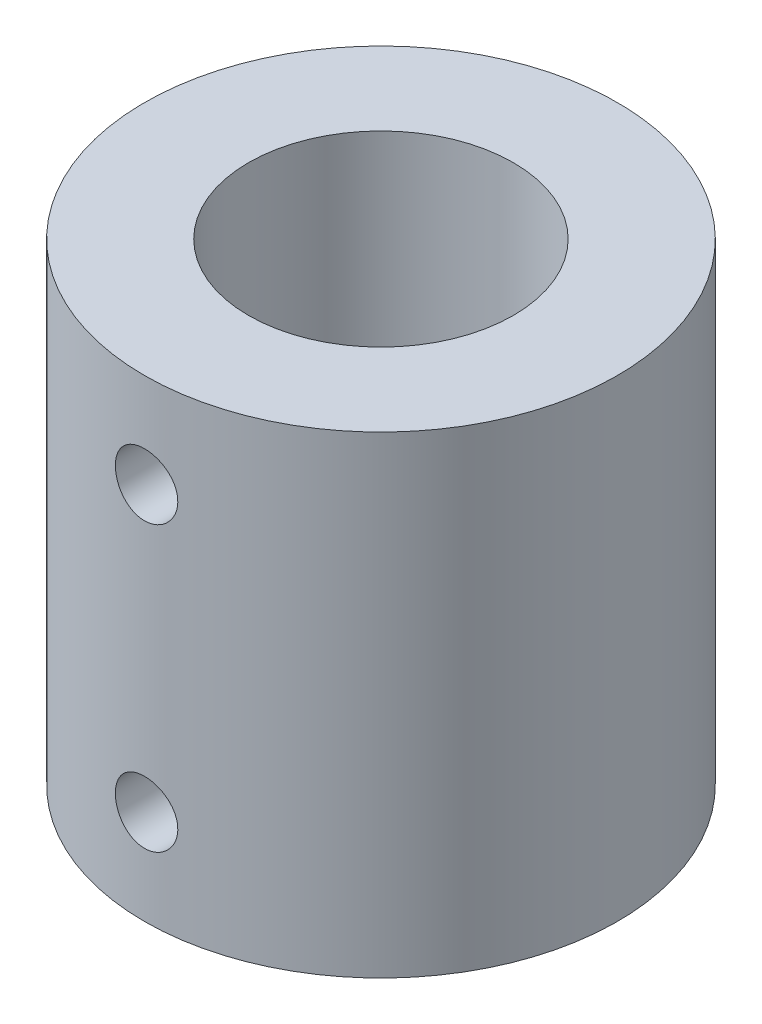
SolidWorks part; units mm, degrees
material "6061 Alloy"
ref_plane "Front Plane" through (0, 0, 0) normal (0, 0, 1) x (1, 0, 0)
ref_plane "Top Plane" through (0, 0, 0) normal (0, 1, 0) x (1, 0, 0)
ref_plane "Right Plane" through (0, 0, 0) normal (1, 0, 0) x (0, 0, -1)
sketch "Sketch1" plane through (0, 0, 0) normal (0, 1, 0) x (1, 0, 0)
  circle A0 centre (0, 0) radius 12.5
  circle A1 centre (0, 0) radius 3
  dimension "D1" = 25
  dimension "D2" = 6
extrude "Boss-Extrude1" add sketch "Sketch1" along normal blind 25
sketch "Sketch2" plane through (0, 25, 0) normal (0, 1, 0) x (1, 0, 0)
  circle A0 centre (0, 0) radius 7
  dimension "D1" = 14
extrude "Cut-Extrude1" cut sketch "Sketch2" against normal blind 12.5
sketch "Sketch3" plane through (0, 0, 0) normal (0, 0, 1) x (1, 0, 0)
  line L0 (0, 20) -> (0, 5) construction
  line L1 (-12.5, 25) -> (-12.5, 0) construction
  circle A0 centre (0, 5) radius 1.65
  circle A1 centre (0, 20) radius 1.65
  point P4 (-12.5, 12.5)
  point P9 (0, 12.5)
  dimension "D1" = 3.3
  dimension "D2" = 15
extrude "Cut-Extrude2" cut sketch "Sketch3" along normal through all contours A1 | A0
